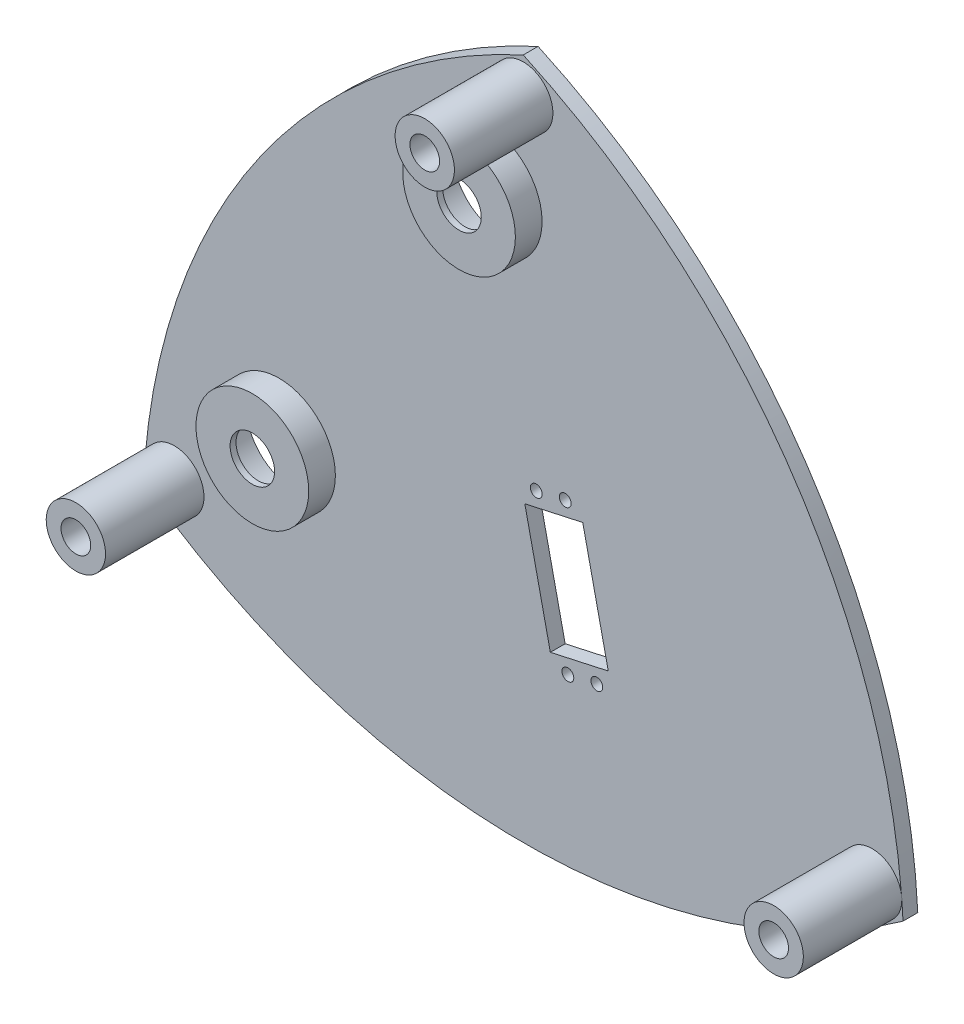
SolidWorks part; units mm, degrees
ref_plane "前视基准面" through (0, 0, 0) normal (0, 0, 1) x (1, 0, 0)
ref_plane "上视基准面" through (0, 0, 0) normal (0, 1, 0) x (1, 0, 0)
ref_plane "右视基准面" through (0, 0, 0) normal (1, 0, 0) x (0, 0, -1)
sketch "草图1" plane through (0, 0, 0) normal (0, 0, 1) x (1, 0, 0)
  line L0 (0, -115) -> (0, 115) construction
  line L2 (0, 0) -> (-128.0227, -73.9139) construction
  line L3 (0, 0) -> (128.0227, -73.9139) construction
  arc A5 (-128.0227, -73.9139) -> (0, 115) centre (91.6989, -84.9783) cw
  arc A6 (-128.0227, -73.9139) -> (128.0227, -73.9139) centre (0, 105) ccw
  arc A7 (128.0227, -73.9139) -> (0, 115) centre (-91.6989, -84.9783) ccw
  circle A8 centre (0, 103) radius 5
  circle A9 centre (-117.6304, -67.9139) radius 5
  circle A10 centre (117.6304, -67.9139) radius 5
  point P8 (-117.6304, -67.9139)
  point P11 (0, 103)
  point P12 (117.6304, -67.9139)
  dimension "D1" = 220
  dimension "D7" = 10
  dimension "D8" = 10
  dimension "D9" = 10
  dimension "D2" = 12
  dimension "D3" = 12
  dimension "D4" = 12
  dimension "D5" = 120
  dimension "D6" = 230
extrude "凸台-拉伸1" add sketch "草图1" along normal blind 5
sketch "草图2" plane through (0, 0, 5) normal (0, 0, 1) x (1, 0, 0)
  circle A0 centre (0, 103) radius 5
  circle A1 centre (0, 103) radius 10
  circle A2 centre (-117.6304, -67.9139) radius 5
  circle A3 centre (-117.6304, -67.9139) radius 10
  circle A4 centre (117.6304, -67.9139) radius 5
  circle A5 centre (117.6304, -67.9139) radius 10
  dimension "D1" = 20
  dimension "D2" = 20
  dimension "D3" = 20
extrude "凸台-拉伸2" add sketch "草图2" along normal blind 33.2
sketch "草图8" plane through (0, 0, 0) normal (0, 0, -1) x (-1, 0, 0)
  circle A1 centre (82.3341, -39.5307) radius 16
  circle A2 centre (12.651, 69.5155) radius 16
  dimension "D1" = 32
  dimension "D2" = 32
extrude "切除-拉伸4" cut sketch "草图8" against normal blind 15
sketch "草图9" plane through (0, 0, 5) normal (0, 0, 1) x (1, 0, 0)
  circle A0 centre (-82.3341, -39.5307) radius 16
  circle A1 centre (-82.3341, -39.5307) radius 19
  circle A2 centre (-12.651, 69.5155) radius 16
  circle A3 centre (-12.651, 69.5155) radius 19
  dimension "D1" = 38
  dimension "D2" = 38
extrude "凸台-拉伸3" add sketch "草图9" along normal blind 9
sketch "草图10" plane through (0, 0, 14) normal (0, 0, 1) x (1, 0, 0)
  circle A0 centre (-82.3341, -39.5307) radius 19
  circle A1 centre (-82.3341, -39.5307) radius 7.5
  circle A2 centre (-12.651, 69.5155) radius 19
  circle A3 centre (-12.651, 69.5155) radius 7.5
  dimension "D1" = 15
  dimension "D2" = 15
extrude "凸台-拉伸4" add sketch "草图10" against normal blind 2
sketch "草图11" plane through (0, 0, 0) normal (0, 0, -1) x (-1, 0, 0)
  line L0 (-9.137, -54.8452) -> (-28.6689, -50.5435)
  line L1 (-28.6689, -50.5435) -> (-20.0655, -11.4797)
  line L2 (-20.0655, -11.4797) -> (-0.5336, -15.7813)
  line L3 (-0.5336, -15.7813) -> (-9.137, -54.8452)
extrude "切除-拉伸5" cut sketch "草图11" against normal blind 10
sketch "草图12" plane through (0, 0, 5) normal (0, 0, 1) x (1, 0, 0)
  circle A0 centre (15.0416, -58.4086) radius 2
  circle A1 centre (24.8075, -56.2577) radius 2
  circle A2 centre (4.3949, -10.0671) radius 2
  circle A3 centre (14.1609, -7.9163) radius 2
extrude "切除-拉伸6" cut sketch "草图12" against normal blind 10
